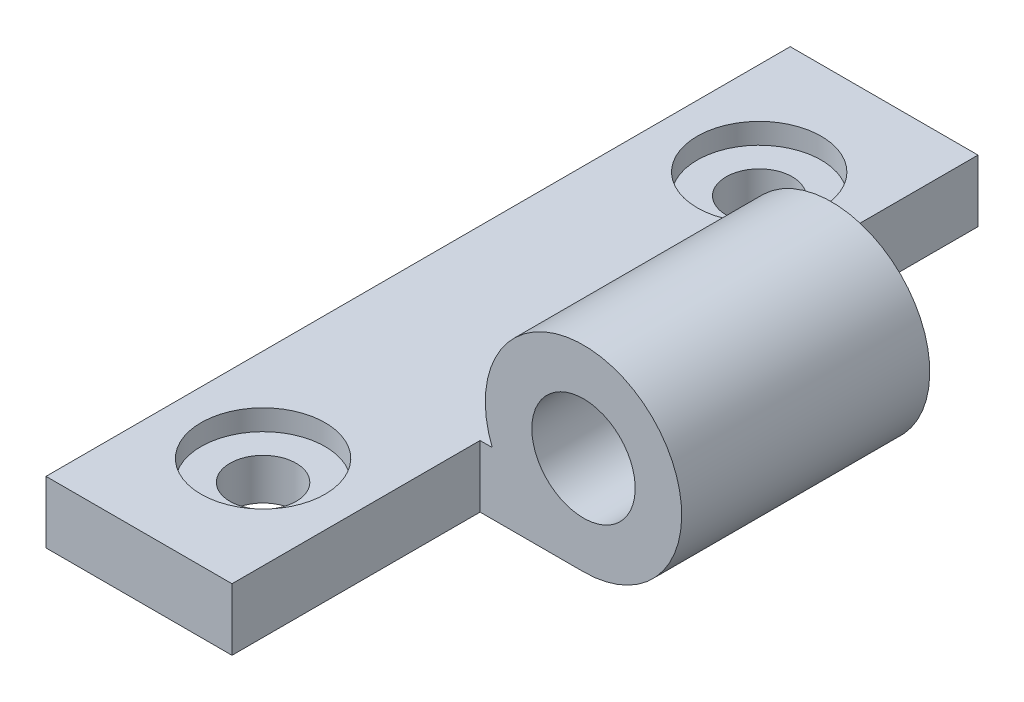
SolidWorks part; units mm, degrees
ref_plane "前视基准面" through (0, 0, 0) normal (0, 0, 1) x (1, 0, 0)
ref_plane "上视基准面" through (0, 0, 0) normal (0, 1, 0) x (1, 0, 0)
ref_plane "右视基准面" through (0, 0, 0) normal (1, 0, 0) x (0, 0, -1)
sketch "草图1" plane through (0, 0, 0) normal (0, 1, 0) x (1, 0, 0)
  line L1 (0, 0) -> (14, 0)
  line L2 (0, 0) -> (0, -36)
  line L3 (0, -36) -> (14, -36)
  line L4 (14, 0) -> (14, -36)
  dimension "D1" = 36
  dimension "D2" = 14
extrude "凸台-拉伸1" add sketch "草图1" along normal blind 3
sketch "草图6" plane through (0, 3, 0) normal (0, 1, 0) x (1, 0, 0)
  line L0 (0, -36) -> (14, -36) construction
  line L1 (0, 0) -> (0, -36) construction
  circle A0 centre (4.5, -6) radius 1.6
  circle A1 centre (4.5, -30) radius 1.6
  dimension "D1" = 3.2
  dimension "D2" = 24
  dimension "D3" = 6
  dimension "D4" = 4.5
extrude "切除-拉伸3" cut sketch "草图6" against normal blind 10
sketch "草图7" plane through (0, 3, 0) normal (0, 1, 0) x (1, 0, 0)
  circle A0 centre (4.5, -6) radius 3
  circle A1 centre (4.5, -30) radius 3
  dimension "D1" = 6
extrude "切除-拉伸4" cut sketch "草图7" against normal blind 1
ref_plane "基准面1" through (0, 0, 12) normal (0, 0, -1) x (-1, 0, 0)
sketch "草图9" plane through (0, 0, 12) normal (0, 0, -1) x (-1, 0, 0)
  line L0 (-14, 3) -> (-14, 0) construction
  line L1 (-14, 0) -> (0, 0) construction
  circle A0 centre (-14, 4.75) radius 4.75
  dimension "D1" = 9.5
extrude "凸台-拉伸2" add sketch "草图9" against normal blind 12
sketch "草图10" plane through (0, 0, 12) normal (0, 0, -1) x (-1, 0, 0)
  circle A0 centre (-14, 4.75) radius 2.5
  circle A1 centre (-14, 4.75) radius 4.75 construction
  dimension "D1" = 5
  dimension "D2" = 0
extrude "切除-拉伸5" cut sketch "草图10" against normal blind 12
sketch "草图11" plane through (0, 0, 0) normal (0, 0, -1) x (-1, 0, 0)
  line L1 (-19.8561, -1.9352) -> (-9.0828, -1.9352)
  line L2 (-19.8561, -1.9352) -> (-19.8561, 8.0069)
  line L3 (-19.8561, 8.0069) -> (-9.0828, 8.0069)
  line L4 (-9.0828, -1.9352) -> (-9.0828, 8.0069)
extrude "切除-拉伸7" cut sketch "草图11" against normal blind 12
sketch "草图12" plane through (0, 0, 36) normal (0, 0, 1) x (1, 0, 0)
  line L1 (19.0806, 4.6096) -> (8.9976, 4.6096)
  line L2 (19.0806, 4.6096) -> (19.0806, -0.5335)
  line L3 (19.0806, -0.5335) -> (8.9976, -0.5335)
  line L4 (8.9976, 4.6096) -> (8.9976, -0.5335)
extrude "切除-拉伸8" cut sketch "草图12" against normal blind 12
